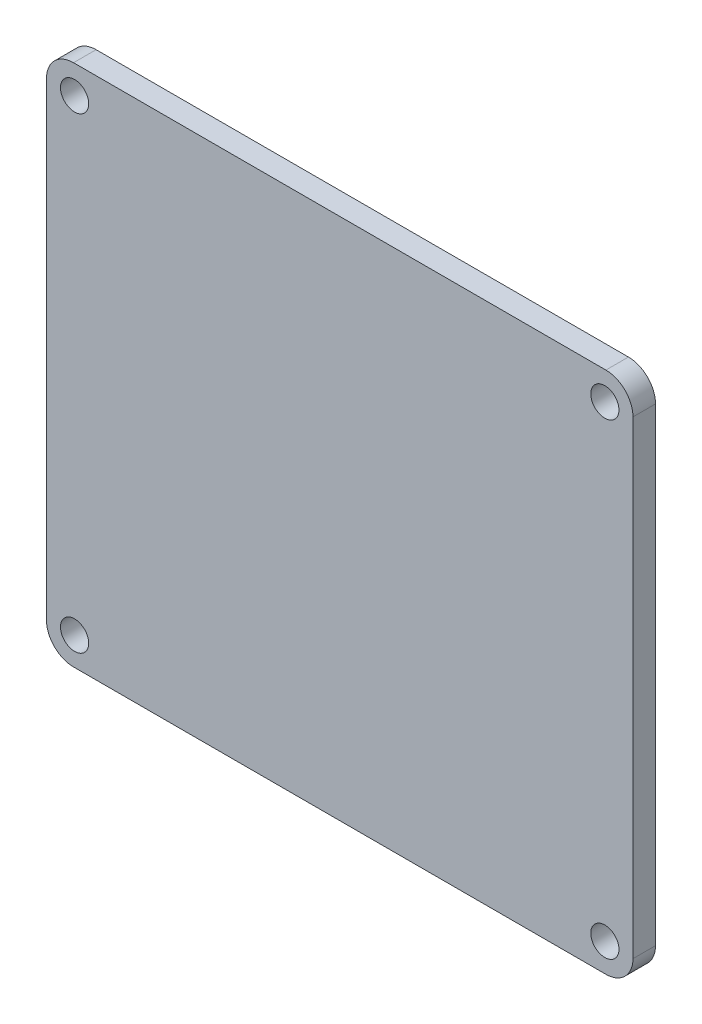
SolidWorks part; units mm, degrees
ref_plane "Front Plane" through (0, 0, 0) normal (0, 0, 1) x (1, 0, 0)
ref_plane "Top Plane" through (0, 0, 0) normal (0, 1, 0) x (1, 0, 0)
ref_plane "Right Plane" through (0, 0, 0) normal (1, 0, 0) x (0, 0, -1)
sketch "Base Sketch" plane through (0, 0, 0) normal (0, 0, 1) x (1, 0, 0)
  line L1 (0, 0) -> (65, 0)
  line L2 (0, 0) -> (0, 58)
  line L3 (0, 58) -> (65, 58)
  line L4 (65, 0) -> (65, 58)
  line L5 (5, 53) -> (60, 53)
  line L6 (5, 53) -> (5, 5)
  line L7 (5, 5) -> (60, 5)
  line L8 (60, 53) -> (60, 5)
  line L9 (5, 48) -> (7, 48)
  line L10 (5, 48) -> (5, 45)
  line L11 (5, 45) -> (7, 45)
  line L12 (7, 48) -> (7, 45)
  line L17 (44, 5) -> (47, 5)
  line L18 (44, 5) -> (44, 7)
  line L19 (44, 7) -> (47, 7)
  line L20 (47, 5) -> (47, 7)
  line L21 (60, 30) -> (58, 30)
  line L22 (60, 30) -> (60, 33)
  line L23 (60, 33) -> (58, 33)
  line L24 (58, 30) -> (58, 33)
  point P9 (32.5, 58)
  point P10 (32.5, 53)
  point P11 (0, 29)
  point P12 (5, 29)
  point P25 (47, 6)
  point P26 (6, 45)
  point P27 (59, 33)
  point P28 (6, 48)
  point P29 (44, 6)
  dimension "D1" = 65
  dimension "D2" = 55
  dimension "D3" = 58
  dimension "D4" = 48
  dimension "D5" = 5
  dimension "D6" = 3
  dimension "D7" = 2
  dimension "D8" = 3
  dimension "D9" = 3
  dimension "D10" = 2
  dimension "D11" = 13
  dimension "D12" = 2
  dimension "D13" = 20
  dimension "D14" = 53
  dimension "D15" = 42
sketch "Mounting Holes" plane through (0, 0, 0) normal (0, 0, 1) x (1, 0, 0)
  line L0 (5, 53) -> (0, 58) construction
  line L1 (60, 53) -> (65, 58) construction
  line L2 (60, 5) -> (65, 0) construction
  line L3 (0, 0) -> (5, 5) construction
  line L4 (3.1155, 54.8845) -> (65, 54.8845) construction
  line L6 (61.8845, 54.8845) -> (61.8845, 0) construction
  line L8 (61.8845, 3.1155) -> (0, 3.1155) construction
  circle A0 centre (3.1155, 54.8845) radius 1.5625
  circle A1 centre (61.8845, 54.8845) radius 1.5625
  circle A2 centre (61.8845, 3.1155) radius 1.5625
  circle A3 centre (3.1155, 3.1155) radius 1.5625
  point P33 (2.5, 55.5)
  dimension "D1" = 3.125
  dimension "D2" = 3.125
  dimension "D3" = 3.125
  dimension "D4" = 3.125
extrude "Boss-Extrude2" add sketch "Base Sketch" along normal blind 2.5 contours L2 L3 L4 L1
extrude "Cut-Extrude5" cut sketch "Mounting Holes" along normal blind 2.5
fillet "Fillet1" radius 3 4 edges at (65, 58, 1.25) (65, 0, 1.25) (0, 0, 1.25) (0, 58, 1.25)
